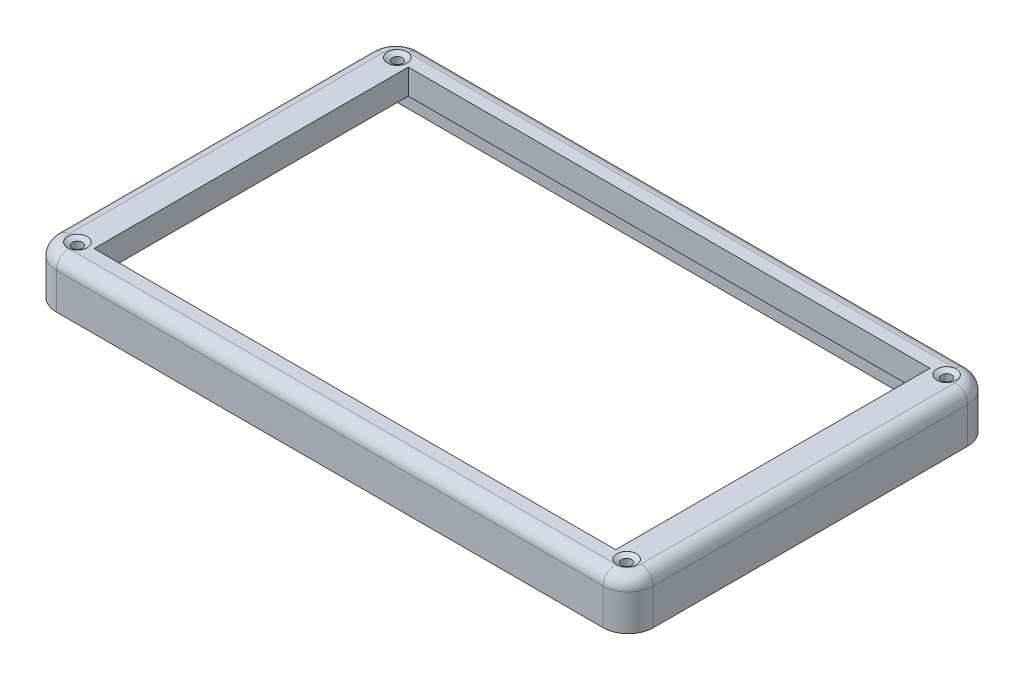
SolidWorks part; units mm, degrees
ref_plane "前视基准面" through (0, 0, 0) normal (0, 0, 1) x (1, 0, 0)
ref_plane "上视基准面" through (0, 0, 0) normal (0, 1, 0) x (1, 0, 0)
ref_plane "右视基准面" through (0, 0, 0) normal (1, 0, 0) x (0, 0, -1)
other "Configuration Table"
sketch "草图1" plane through (0, 0, 0) normal (0, 1, 0) x (1, 0, 0)
  line L0 (-95, 58) -> (95, 58)
  line L1 (-83, -50) -> (83, -50)
  line L2 (-83, -50) -> (-83, 50)
  line L3 (-83, 50) -> (83, 50)
  line L4 (83, -50) -> (83, 50)
  line L5 (-83, -50) -> (83, 50) construction
  line L6 (-83, 50) -> (83, -50) construction
  line L7 (-91, -54) -> (91, -54)
  line L8 (-91, -54) -> (-91, 54)
  line L9 (-91, 54) -> (91, 54)
  line L10 (91, -54) -> (91, 54)
  line L11 (-91, -54) -> (91, 54) construction
  line L12 (-91, 54) -> (91, -54) construction
  line L13 (95, -58) -> (95, 58)
  line L14 (-95, -58) -> (95, -58)
  line L15 (-95, -58) -> (-95, 58)
  point P0 (0, 0)
  point P6 (0, 0)
  dimension "D1" = 166
  dimension "D2" = 100
  dimension "D3" = 8
  dimension "D4" = 4
  dimension "D5" = 4
extrude "凸台-拉伸2" add sketch "草图1" along normal blind 8 contours L1 L4 L3 L2 | L0 L13 L14 L15
sketch "草图2" plane through (0, 0, 0) normal (0, -1, 0) x (1, 0, 0)
  line L0 (-91, 54) -> (-91, -54)
  line L1 (-95, 58) -> (95, 58)
  line L2 (-95, 58) -> (-95, -58)
  line L3 (-95, -58) -> (95, -58)
  line L4 (95, 58) -> (95, -58)
  line L5 (-91, -54) -> (91, -54)
  line L6 (91, 54) -> (91, -54)
  line L7 (-91, 54) -> (91, 54)
  dimension "D1" = 4
extrude "凸台-拉伸3" add sketch "草图2" along normal blind 7.5
fillet "圆角1" radius 8 4 edges at (95, 0.25, 58) (95, 0.25, -58) (-95, 0.25, -58) (-95, 0.25, 58)
sketch "草图3" plane through (-95, 0, 0) normal (-1, 0, 0) x (0, 0, 1)
  line L0 (50, -7.5) -> (-50, -7.5) construction
  line L1 (-7.5, 0) -> (7.5, 0)
  line L2 (-7.5, 0) -> (-7.5, -7.5)
  line L3 (-7.5, -7.5) -> (7.5, -7.5)
  line L4 (7.5, 0) -> (7.5, -7.5)
  line L5 (-7.5, 0) -> (7.5, -7.5) construction
  line L6 (-7.5, -7.5) -> (7.5, 0) construction
  point P0 (0, -3.75)
  dimension "D1" = 15
  dimension "D2" = 7.5
extrude "切除-拉伸1" cut sketch "草图3" against normal blind 7.5
sketch "草图4" plane through (0, 0, -58) normal (0, 0, -1) x (-1, 0, 0)
  line L0 (-95, -7.5) -> (-95, 8) construction
  line L1 (-70, -1) -> (-54, -1)
  line L2 (-70, -1) -> (-70, -4)
  line L3 (-70, -4) -> (-54, -4)
  line L4 (-54, -1) -> (-54, -4)
  line L5 (87, 8) -> (-87, 8) construction
  dimension "D1" = 3
  dimension "D2" = 25
  dimension "D3" = 16
  dimension "D4" = 9
extrude "切除-拉伸2" cut sketch "草图4" against normal blind 35.5 contours L1 L4 L3 L2
sketch "草图5" plane through (0, 8, 0) normal (0, 1, 0) x (1, 0, 0)
  line L0 (-87, 58) -> (87, 58) construction
  line L1 (-95, -50) -> (-95, 50) construction
  line L2 (0, 0) -> (-95, 0) construction
  line L3 (0, 0) -> (0, 58) construction
  circle A0 centre (-87.4, 50.9) radius 1.6
  circle A1 centre (-87.4, -50.9) radius 1.6
  circle A2 centre (87.4, -50.9) radius 1.6
  circle A3 centre (87.4, 50.9) radius 1.6
  dimension "D1" = 3.2
  dimension "D2" = 7.1
  dimension "D3" = 7.6
extrude "切除-拉伸3" cut sketch "草图5" against normal blind 35.5
chamfer "倒角1" distance 1.5 angle 30 4 edges at (87.4, 8, 52.5) (-87.4, 8, 49.3) (-87.4, 8, -49.3) (87.4, 8, -52.5)
sketch "草图6" plane through (-95, 0, 0) normal (-1, 0, 0) x (0, 0, 1)
  line L0 (-43.5, -11.6) -> (-43.5, -3.6) construction
  line L1 (-43.5, -7.6) -> (-21.5, -7.6)
  line L2 (-43.5, -7.6) -> (-43.5, -5.1)
  line L3 (-43.5, -5.1) -> (-21.5, -5.1)
  line L4 (-21.5, -7.6) -> (-21.5, -5.1)
  line L5 (-22, -5.1) -> (-43.5, -5.1) construction
  line L6 (-43.5, -5.1) -> (-21.5, -7.6) construction
  line L7 (-43.5, -7.6) -> (-21.5, -5.1) construction
  point P8 (-32.5, -6.35)
  dimension "D1" = 22
extrude "切除-拉伸4" cut sketch "草图6" against normal blind 4
fillet "圆角2" radius 4 8 edges at (-92.6569, 8, -55.6569) (-95, 8, 0) (-92.6569, 8, 55.6569) (0, 8, 58) (92.6569, 8, 55.6569) (95, 8, 0) (92.6569, 8, -55.6569) (0, 8, -58)
